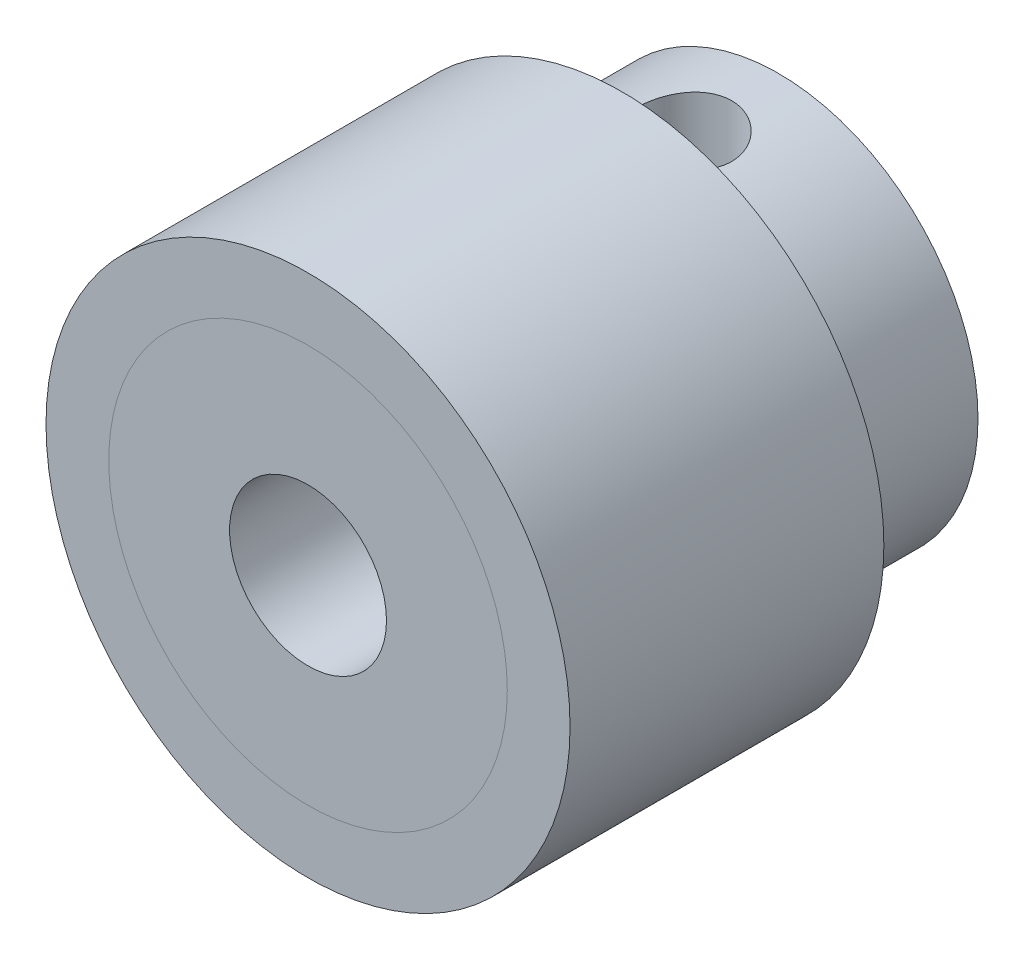
SolidWorks part; units mm, degrees
ref_plane "Front Plane" through (0, 0, 0) normal (0, 0, 1) x (1, 0, 0)
ref_plane "Top Plane" through (0, 0, 0) normal (0, 1, 0) x (1, 0, 0)
ref_plane "Right Plane" through (0, 0, 0) normal (1, 0, 0) x (0, 0, -1)
sketch "Sketch1" plane through (0, 0, 0) normal (0, 0, 1) x (1, 0, 0)
  circle A0 centre (0, 0) radius 6.35
  circle A1 centre (0, 0) radius 2.5
  dimension "D1" = 12.7
  dimension "D2" = 5
extrude "Boss-Extrude1" add sketch "Sketch1" along normal blind 15
sketch "Sketch2" plane through (0, 0, 0) normal (0, 1, 0) x (1, 0, 0)
  circle A0 centre (0, -3) radius 1.5
  dimension "D2" = 3
  dimension "D1" = 3
extrude "Cut-Extrude1" cut sketch "Sketch2" along normal through all
sketch "Sketch3" plane through (0, 0, 15) normal (0, 0, 1) x (1, 0, 0)
  circle A0 centre (0, 0) radius 6.35 construction
  circle A1 centre (0, 0) radius 6.35
  circle A2 centre (0, 0) radius 8.35
  dimension "D1" = 2
extrude "Boss-Extrude2" add sketch "Sketch3" against normal blind 10 separate body
